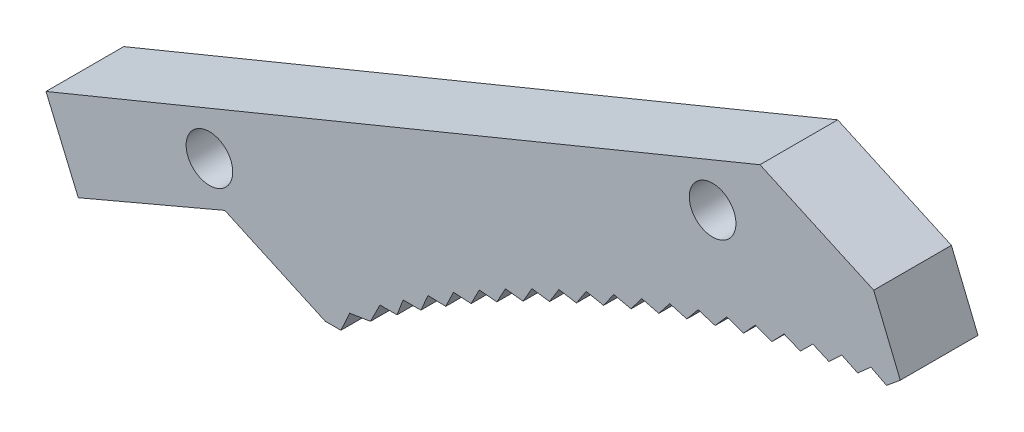
SolidWorks part; units mm, degrees
material "아크릴(내충격성)"
ref_plane "정면" through (0, 0, 0) normal (0, 0, 1) x (1, 0, 0)
ref_plane "윗면" through (0, 0, 0) normal (0, 1, 0) x (1, 0, 0)
ref_plane "우측면" through (0, 0, 0) normal (1, 0, 0) x (0, 0, -1)
sketch "스케치1" plane through (0, 0, 0) normal (0, 0, 1) x (1, 0, 0)
  line L0 (0, 0) -> (22, 0) construction
  line L1 (0, 5) -> (22, 5)
  line L2 (0, -5) -> (22, -5)
  line L7 (20.05, 5) -> (23.9914, -4.5863) construction
  line L8 (20.05, 5) -> (75.5427, 27.8158) construction
  line L9 (23.9914, -4.5863) -> (79.4841, 18.2295) construction
  line L10 (75.5427, 27.8158) -> (79.4841, 18.2295) construction
  line L11 (20.05, 5) -> (70.4559, 25.7244)
  line L12 (70.4559, 25.7244) -> (77.7729, 22.3914)
  line L13 (77.7729, 22.3914) -> (79.4841, 18.2295)
  line L14 (42.489, 3.019) -> (43.4982, 3.019)
  line L15 (42.489, 3.019) -> (36.0251, 5.9632)
  line L16 (36.0251, 5.9632) -> (26.6014, 1.9564)
  line L17 (43.4982, 3.019) -> (44.0621, 4.2539)
  line L18 (44.0621, 4.2539) -> (45.4024, 4.4704)
  line L19 (45.4024, 4.4704) -> (46.0087, 5.6852)
  line L20 (46.0087, 5.6852) -> (47.1079, 5.6852)
  line L21 (47.1079, 5.6852) -> (47.4984, 6.7127)
  line L22 (47.4984, 6.7127) -> (48.641, 6.7127)
  line L23 (48.641, 6.7127) -> (49.103, 7.7576)
  line L24 (49.103, 7.7576) -> (50.2451, 7.7264)
  line L25 (50.2451, 7.7264) -> (50.7356, 8.7582)
  line L26 (50.7356, 8.7582) -> (51.8764, 8.6958)
  line L27 (51.8764, 8.6958) -> (52.3949, 9.7138)
  line L28 (26.6014, 1.9564) -> (22, -5)
  line L29 (52.3949, 9.7138) -> (53.5336, 9.6202)
  line L30 (53.5336, 9.6202) -> (54.0798, 10.6237)
  line L31 (54.0798, 10.6237) -> (55.2154, 10.4989)
  line L32 (55.2154, 10.4989) -> (55.7889, 11.4871)
  line L33 (55.7889, 11.4871) -> (56.9207, 11.3313)
  line L34 (19.8104, 5.5827) -> (70.4687, 26.4108) construction
  line L35 (70.4687, 26.4108) -> (78.2608, 22.8615) construction
  line L36 (78.2608, 22.8615) -> (80.3902, 17.6823) construction
  line L37 (56.9207, 11.3313) -> (57.5209, 12.3034)
  line L38 (57.5209, 12.3034) -> (58.6481, 12.1167)
  line L39 (58.6481, 12.1167) -> (59.2747, 13.0721)
  line L40 (59.2747, 13.0721) -> (60.3963, 12.8546)
  line L41 (60.3963, 12.8546) -> (61.0488, 13.7925)
  line L42 (61.0488, 13.7925) -> (62.1641, 13.5444)
  line L43 (62.1641, 13.5444) -> (62.842, 14.4641)
  line L44 (62.842, 14.4641) -> (63.95, 14.1857)
  line L45 (63.95, 14.1857) -> (64.6528, 15.0864)
  line L46 (64.6528, 15.0864) -> (65.7529, 14.7778)
  line L47 (65.7529, 14.7778) -> (66.4801, 15.659)
  line L48 (66.4801, 15.659) -> (67.5712, 15.3203)
  line L49 (67.5712, 15.3203) -> (68.3222, 16.1813)
  line L50 (68.3222, 16.1813) -> (69.4037, 15.813)
  line L51 (69.4037, 15.813) -> (70.1655, 16.6501)
  line L52 (70.1655, 16.6501) -> (71.2242, 16.2497)
  line L53 (71.2242, 16.2497) -> (72.0083, 17.066)
  line L54 (72.0083, 17.066) -> (73.0558, 16.6372)
  line L55 (73.0558, 16.6372) -> (73.8616, 17.432)
  line L56 (73.8616, 17.432) -> (74.8971, 16.9751)
  line L57 (74.8971, 16.9751) -> (75.7241, 17.7478)
  line L58 (75.7241, 17.7478) -> (76.7469, 17.2631)
  line L59 (76.7469, 17.2631) -> (77.5945, 18.0133)
  line L60 (77.5945, 18.0133) -> (78.6038, 17.5012)
  line L61 (78.6038, 17.5012) -> (79.4841, 18.2295)
  line L62 (36.0251, 5.9632) -> (34.0539, 10.7577)
  arc A0 (0, 5) -> (0, -5) centre (0, 0) ccw
  arc A1 (22, -5) -> (22, 5) centre (22, 0) ccw
  circle A2 centre (22, 0) radius 1.5
  circle A3 centre (0, 0) radius 1.5
  arc A4 (42.489, 3.019) -> (79.4841, 18.2295) centre (86.4954, -51.4185) cw
  arc A5 (42.885, 2.529) -> (80.3902, 17.6823) centre (86.4954, -51.4185) cw construction
  circle A6 centre (35.0395, 8.3605) radius 1.5
  circle A7 centre (67.4103, 21.6697) radius 1.5
  point P3 (11, 0)
  dimension "D2" = 10
  dimension "D10" = 3
  dimension "D7" = 70
  dimension "D1" = 22
  dimension "D3" = 157.65
  dimension "D4" = 1.95
  dimension "D5" = 60
  dimension "D6" = 40
  dimension "D8" = 4.5
  dimension "D9" = 5.5
  dimension "D11" = 10.2402
  dimension "D12" = 2
  dimension "D13" = 0.63
extrude "보스-돌출1" add sketch "스케치1" along normal blind 5
sketch "스케치2" plane through (0, 0, 5) normal (0, 0, 1) x (1, 0, 0)
  line L0 (26.6014, 1.9564) -> (24.525, 6.8399)
  line L51 (77.7729, 22.3914) -> (70.4559, 25.7244)
  line L52 (70.4559, 25.7244) -> (20.05, 5)
  line L53 (20.05, 5) -> (0, 5)
  line L54 (0, -5) -> (22, -5)
  line L55 (22, -5) -> (26.6014, 1.9564)
  line L56 (26.6014, 1.9564) -> (36.0251, 5.9632)
  line L57 (36.0251, 5.9632) -> (42.489, 3.019)
  line L58 (42.489, 3.019) -> (43.4982, 3.019)
  line L59 (43.4982, 3.019) -> (44.0621, 4.2539)
  line L60 (44.0621, 4.2539) -> (45.4024, 4.4704)
  line L61 (45.4024, 4.4704) -> (46.0087, 5.6852)
  line L62 (46.0087, 5.6852) -> (47.1079, 5.6852)
  line L63 (47.1079, 5.6852) -> (47.4984, 6.7127)
  line L64 (47.4984, 6.7127) -> (48.641, 6.7127)
  line L65 (48.641, 6.7127) -> (49.103, 7.7576)
  line L66 (49.103, 7.7576) -> (50.2451, 7.7264)
  line L67 (50.2451, 7.7264) -> (50.7356, 8.7582)
  line L68 (50.7356, 8.7582) -> (51.8764, 8.6958)
  line L69 (51.8764, 8.6958) -> (52.3949, 9.7138)
  line L70 (52.3949, 9.7138) -> (53.5336, 9.6202)
  line L71 (53.5336, 9.6202) -> (54.0798, 10.6237)
  line L72 (54.0798, 10.6237) -> (55.2154, 10.4989)
  line L73 (55.2154, 10.4989) -> (55.7889, 11.4871)
  line L74 (55.7889, 11.4871) -> (56.9207, 11.3313)
  line L75 (56.9207, 11.3313) -> (57.5209, 12.3034)
  line L76 (57.5209, 12.3034) -> (58.6481, 12.1167)
  line L77 (58.6481, 12.1167) -> (59.2747, 13.0721)
  line L78 (59.2747, 13.0721) -> (60.3963, 12.8546)
  line L79 (60.3963, 12.8546) -> (61.0488, 13.7925)
  line L80 (61.0488, 13.7925) -> (62.1641, 13.5444)
  line L81 (62.1641, 13.5444) -> (62.842, 14.4641)
  line L82 (62.842, 14.4641) -> (63.95, 14.1857)
  line L83 (63.95, 14.1857) -> (64.6528, 15.0864)
  line L84 (64.6528, 15.0864) -> (65.7529, 14.7778)
  line L85 (65.7529, 14.7778) -> (66.4801, 15.659)
  line L86 (66.4801, 15.659) -> (67.5712, 15.3203)
  line L87 (67.5712, 15.3203) -> (68.3222, 16.1813)
  line L88 (68.3222, 16.1813) -> (69.4037, 15.813)
  line L89 (69.4037, 15.813) -> (70.1655, 16.6501)
  line L90 (70.1655, 16.6501) -> (71.2242, 16.2497)
  line L91 (71.2242, 16.2497) -> (72.0083, 17.066)
  line L92 (72.0083, 17.066) -> (73.0558, 16.6372)
  line L93 (73.0558, 16.6372) -> (73.8616, 17.432)
  line L94 (73.8616, 17.432) -> (74.8971, 16.9751)
  line L95 (74.8971, 16.9751) -> (75.7241, 17.7478)
  line L96 (75.7241, 17.7478) -> (76.7469, 17.2631)
  line L97 (76.7469, 17.2631) -> (77.5945, 18.0133)
  line L98 (77.5945, 18.0133) -> (78.6038, 17.5012)
  line L99 (78.6038, 17.5012) -> (79.4841, 18.2295)
  line L100 (79.4841, 18.2295) -> (77.7729, 22.3914)
  line L102 (24.525, 6.8399) -> (20.05, 5)
  line L103 (20.05, 5) -> (0, 5)
  line L104 (0, -5) -> (22, -5)
  line L105 (22, -5) -> (26.6014, 1.9564)
  arc A1 (0, 5) -> (0, -5) centre (0, 0) ccw
  arc A2 (0, 5) -> (0, -5) centre (0, 0) ccw
  dimension "D1" = 0
extrude "컷-돌출1" cut sketch "스케치2" against normal through all
